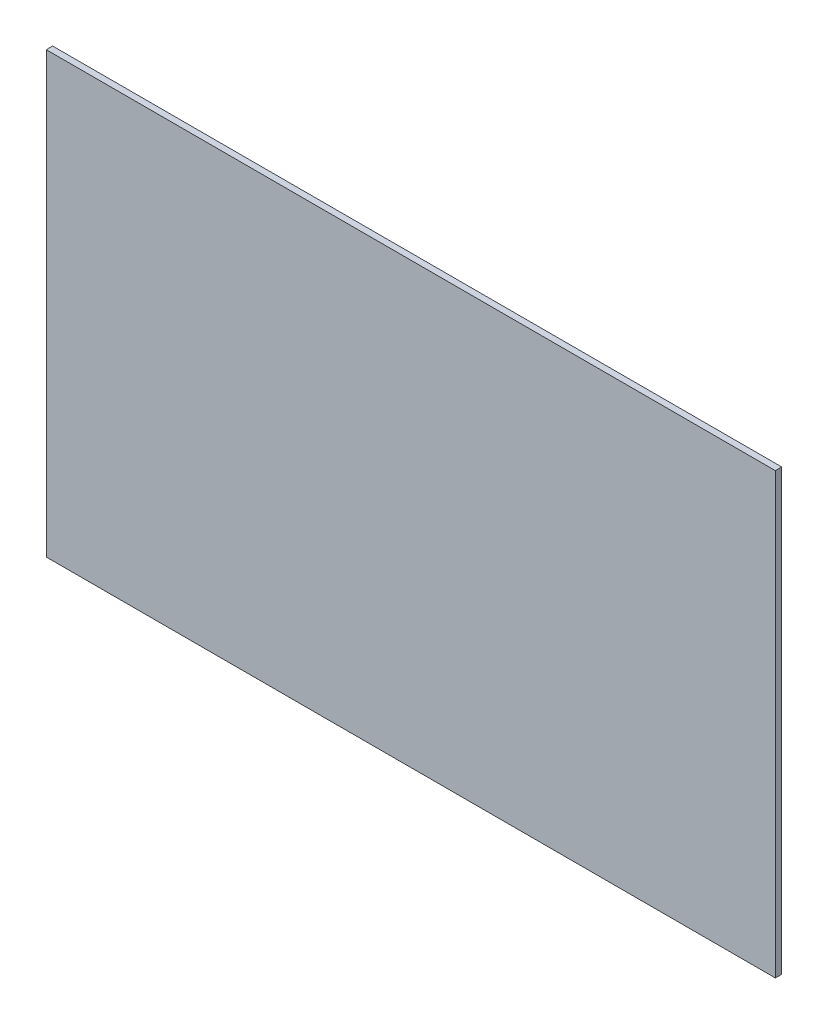
SolidWorks part; units mm, degrees
material "고무"
ref_plane "정면" through (0, 0, 0) normal (0, 0, 1) x (1, 0, 0)
ref_plane "윗면" through (0, 0, 0) normal (0, 1, 0) x (1, 0, 0)
ref_plane "우측면" through (0, 0, 0) normal (1, 0, 0) x (0, 0, -1)
sketch "스케치1" plane through (0, 0, 0) normal (0, 0, 1) x (1, 0, 0)
  line L1 (-114.5, 69) -> (114.5, 69)
  line L2 (-114.5, 69) -> (-114.5, -69)
  line L3 (-114.5, -69) -> (114.5, -69)
  line L4 (114.5, 69) -> (114.5, -69)
extrude "보스-돌출1" add sketch "스케치1" along normal blind 2
